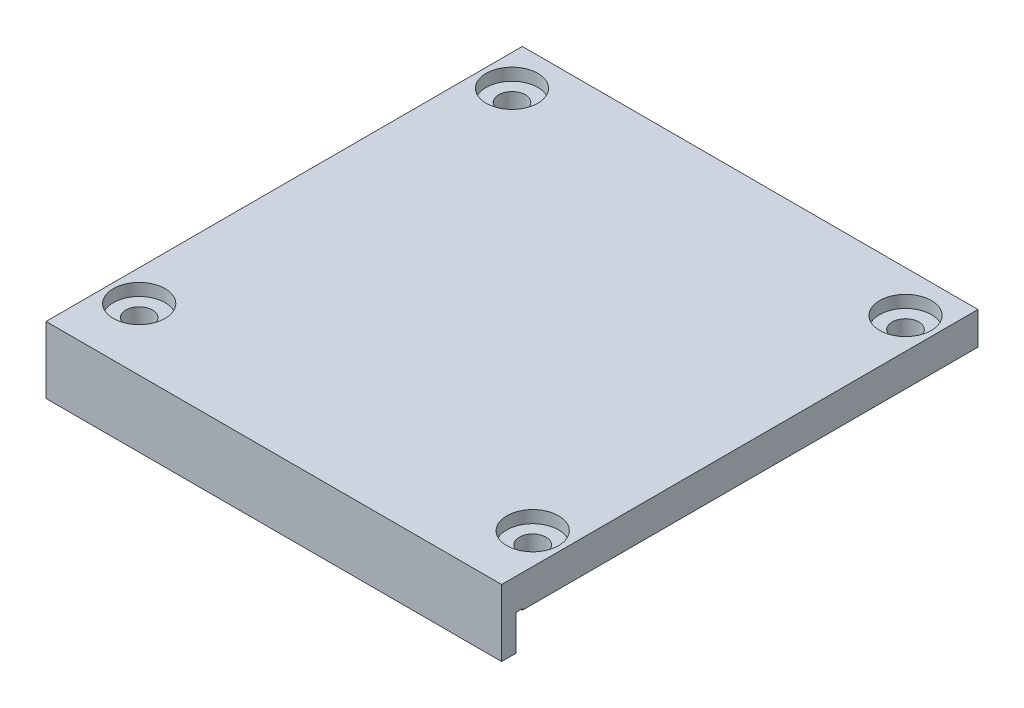
SolidWorks part; units mm, degrees
ref_plane "Front Plane" through (0, 0, 0) normal (0, 0, 1) x (1, 0, 0)
ref_plane "Top Plane" through (0, 0, 0) normal (0, 1, 0) x (1, 0, 0)
ref_plane "Right Plane" through (0, 0, 0) normal (1, 0, 0) x (0, 0, -1)
sketch "Sketch1" plane through (0, 0, 0) normal (0, 1, 0) x (1, 0, 0)
  line L1 (-27.94, -27.94) -> (27.94, -27.94)
  line L2 (-27.94, -27.94) -> (-27.94, 27.94)
  line L3 (-27.94, 27.94) -> (27.94, 27.94)
  line L4 (27.94, -27.94) -> (27.94, 27.94)
  line L5 (-27.94, -27.94) -> (27.94, 27.94) construction
  line L6 (-27.94, 27.94) -> (27.94, -27.94) construction
  point P0 (0, 0)
  dimension "D1" = 55.88
  dimension "D2" = 55.88
extrude "Boss-Extrude1" add sketch "Sketch1" along normal blind 4
hole_wizard "CBORE for #4 Button Head Cap Screw1" positions "Sketch3" profile "Sketch2" counterbore size "#4" standard "ANSI Inch" end condition up to next
sketch "Sketch3" plane through (0, 4, 0) normal (0, 1, 0) x (1, 0, 0)
  line L0 (27.94, 27.94) -> (-27.94, 27.94) construction
  line L1 (-27.94, 27.94) -> (-27.94, -27.94) construction
  line L2 (27.94, -27.94) -> (27.94, 27.94) construction
  line L3 (-27.94, -27.94) -> (27.94, -27.94) construction
  point P0 (-24.13, 22.86)
  point P5 (24.13, 22.86)
  point P7 (24.13, -22.86)
  point P9 (-24.13, -22.86)
  dimension "D1" = 5.08
  dimension "D2" = 3.81
  dimension "D3" = 5.08
  dimension "D4" = 3.81
  dimension "D5" = 5.08
  dimension "D6" = 3.81
  dimension "D7" = 3.81
  dimension "D8" = 5.08
sketch "Sketch2" plane through (-24.13, 4, -22.86) normal (1, 0, 0) x (0, 0, 1)
  line L0 (0, 0) -> (0, 4)
  line L1 (0, 4) -> (1.6319, 4)
  line L3 (1.6319, 4) -> (1.6319, 1.4986)
  line L4 (1.6319, 1.4986) -> (3.175, 1.4986)
  line L5 (3.175, 1.4986) -> (3.175, 0)
  line L7 (3.175, 0) -> (0, 0)
  line L11 (0, -6.35) -> (0, 107.95) construction
  dimension "Thru Hole Dia." = 3.2639
  dimension "Thru Hole Depth" = 4
  dimension "C'Bore Dia." = 6.35
  dimension "C'Bore Depth" = 1.4986
sketch "Sketch4" plane through (0, 0, 27.94) normal (0, 0, 1) x (1, 0, 0)
  line L0 (-27.94, 4) -> (27.94, 4)
  line L1 (-27.94, 4) -> (-27.94, -4.1846)
  line L2 (27.94, 4) -> (27.94, -4.1846)
  line L3 (-27.94, -4.1846) -> (27.94, -4.1846)
extrude "Boss-Extrude2" add sketch "Sketch4" along normal blind 2.54
sketch "Sketch5" plane through (0, 0, 27.94) normal (0, 0, -1) x (-1, 0, 0)
  line L0 (-27.94, -4.1846) -> (27.94, -4.1846)
  line L1 (-27.94, -4.1846) -> (-27.94, 0.1643)
  line L2 (27.94, -4.1846) -> (27.94, 0.1643)
  line L3 (-27.94, 0.1643) -> (27.94, 0.1643)
extrude "Cut-Extrude1" cut sketch "Sketch5" against normal blind 0.762
